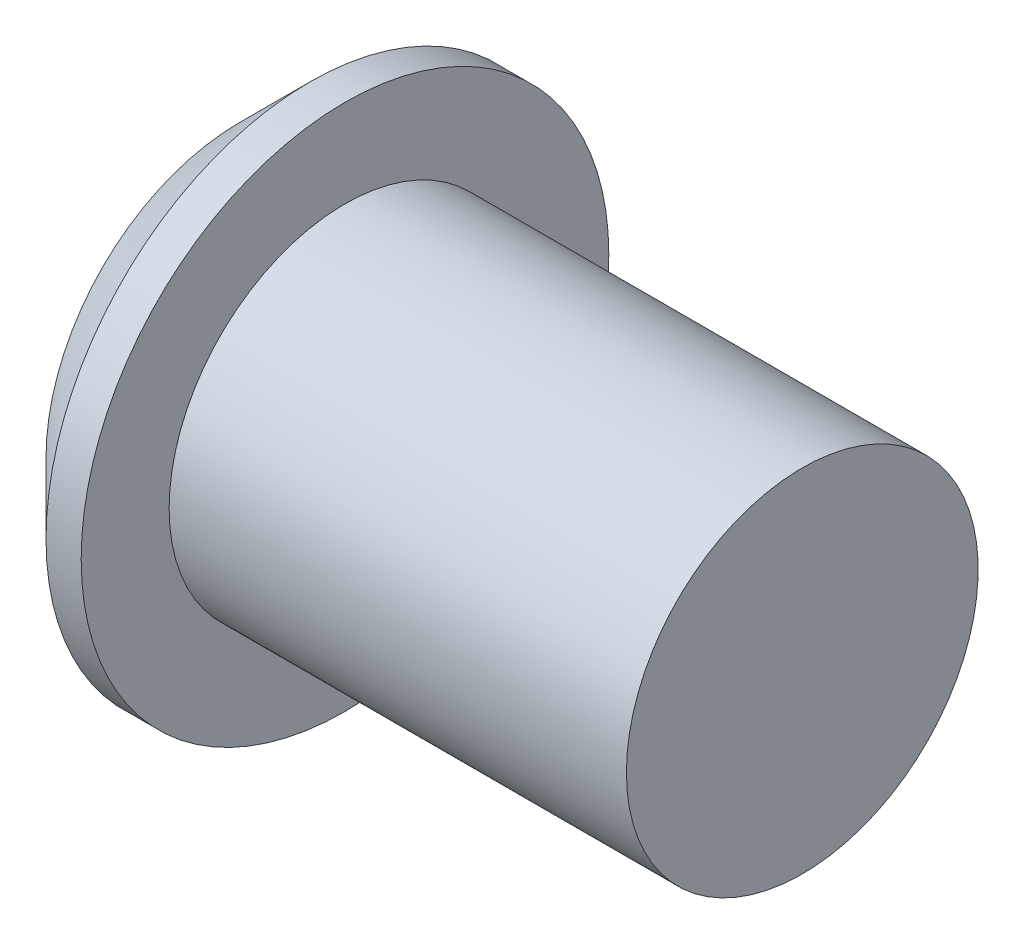
SolidWorks part; units mm, degrees
ref_plane "Front Plane" through (0, 0, 0) normal (0, 0, 1) x (1, 0, 0)
ref_plane "Top Plane" through (0, 0, 0) normal (0, 1, 0) x (1, 0, 0)
ref_plane "Right Plane" through (0, 0, 0) normal (1, 0, 0) x (0, 0, -1)
sketch "Sketch1" plane through (0, 0, 0) normal (1, 0, 0) x (0, 0, -1)
  circle A0 centre (0, 0) radius 5
  dimension "D1" = 10
extrude "Boss-Extrude1" add sketch "Sketch1" along normal blind 13
sketch "Sketch2" plane through (0, 0, 0) normal (-1, 0, 0) x (0, 0, 1)
  circle A0 centre (0, 0) radius 7.5
  dimension "D1" = 15
extrude "Boss-Extrude2" add sketch "Sketch2" along normal blind 3
chamfer "Chamfer1" distance 2 angle 45 1 edges at (-3, 0, 7.5)
